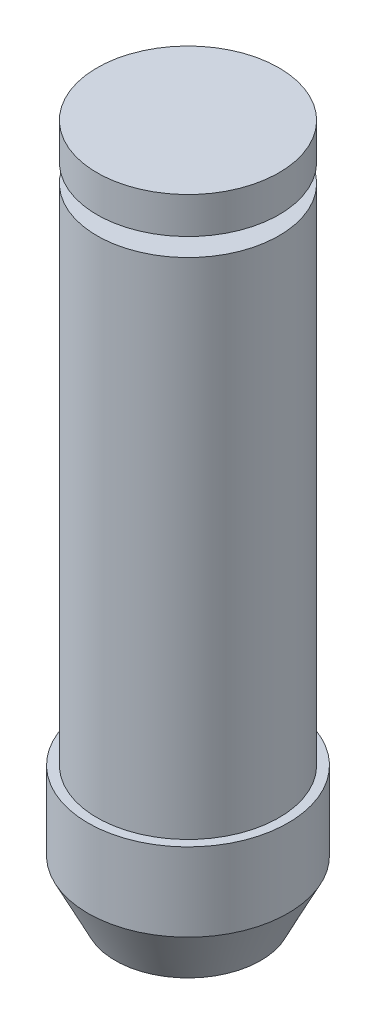
SolidWorks part; units mm, degrees
ref_plane "前视基准面" through (0, 0, 0) normal (0, 0, 1) x (1, 0, 0)
ref_plane "上视基准面" through (0, 0, 0) normal (0, 1, 0) x (1, 0, 0)
ref_plane "右视基准面" through (0, 0, 0) normal (1, 0, 0) x (0, 0, -1)
sketch "草图1" plane through (0, 0, 0) normal (0, 0, 1) x (1, 0, 0)
  line L0 (0, 0) -> (-40, 0)
  line L1 (-40, 0) -> (-55, 30)
  line L2 (-55, 30) -> (-55, 73)
  line L3 (-55, 73) -> (-50, 73)
  line L4 (-50, 73) -> (-50, 350)
  line L5 (-50, 350) -> (-35, 350)
  line L6 (-35, 350) -> (-35, 360)
  line L7 (0, -1000) -> (0, 49000) construction
  line L8 (-35, 360) -> (-50, 360)
  line L9 (-50, 360) -> (-50, 380)
  line L10 (-50, 380) -> (0, 380)
  line L11 (0, 380) -> (0, 0)
  dimension "D1" = 40
  dimension "D2" = 55
  dimension "D3" = 30
  dimension "D4" = 43
  dimension "D5" = 50
  dimension "D6" = 277
  dimension "D7" = 10
  dimension "D8" = 35
  dimension "D9" = 50
  dimension "D10" = 380
revolve "旋转1" add sketch "草图1" angle 360 about L7
